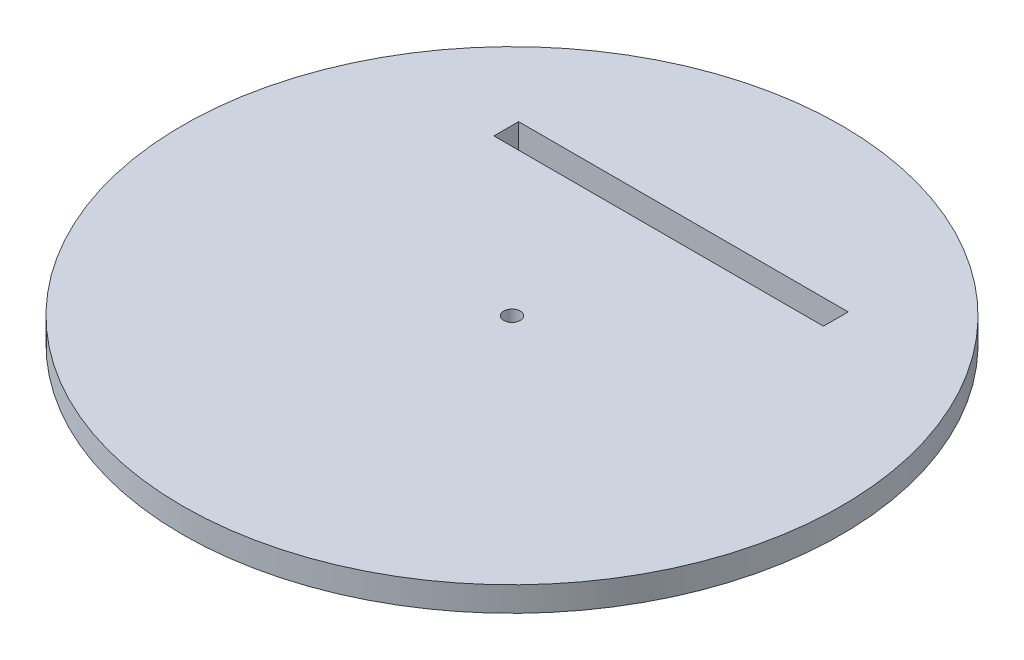
SolidWorks part; units mm, degrees
ref_plane "Front Plane" through (0, 0, 0) normal (0, 0, 1) x (1, 0, 0)
ref_plane "Top Plane" through (0, 0, 0) normal (0, 1, 0) x (1, 0, 0)
ref_plane "Right Plane" through (0, 0, 0) normal (1, 0, 0) x (0, 0, -1)
sketch "Sketch1" plane through (0, 0, 0) normal (0, 1, 0) x (1, 0, 0)
  circle A0 centre (0, 0) radius 40
  dimension "D1" = 80
extrude "Boss-Extrude1" add sketch "Sketch1" along normal blind 3
sketch "Sketch2" plane through (0, 3, 0) normal (0, 1, 0) x (1, 0, 0)
  circle A0 centre (0, 0) radius 1
  circle A1 centre (0, 0) radius 40 construction
  dimension "D1" = 2
extrude "Cut-Extrude1" cut sketch "Sketch2" against normal blind 3
sketch "Sketch3" plane through (0, 3, 0) normal (0, 1, 0) x (1, 0, 0)
  line L0 (0, 0) -> (0, 35.6057) construction
  line L1 (-20, 20.8028) -> (20, 20.8028)
  line L2 (-20, 20.8028) -> (-20, 17.8028)
  line L3 (-20, 17.8028) -> (20, 17.8028)
  line L4 (20, 20.8028) -> (20, 17.8028)
  point P7 (0, 17.8028)
  dimension "D1" = 3
  dimension "D2" = 40
extrude "Cut-Extrude2" cut sketch "Sketch3" against normal blind 10
